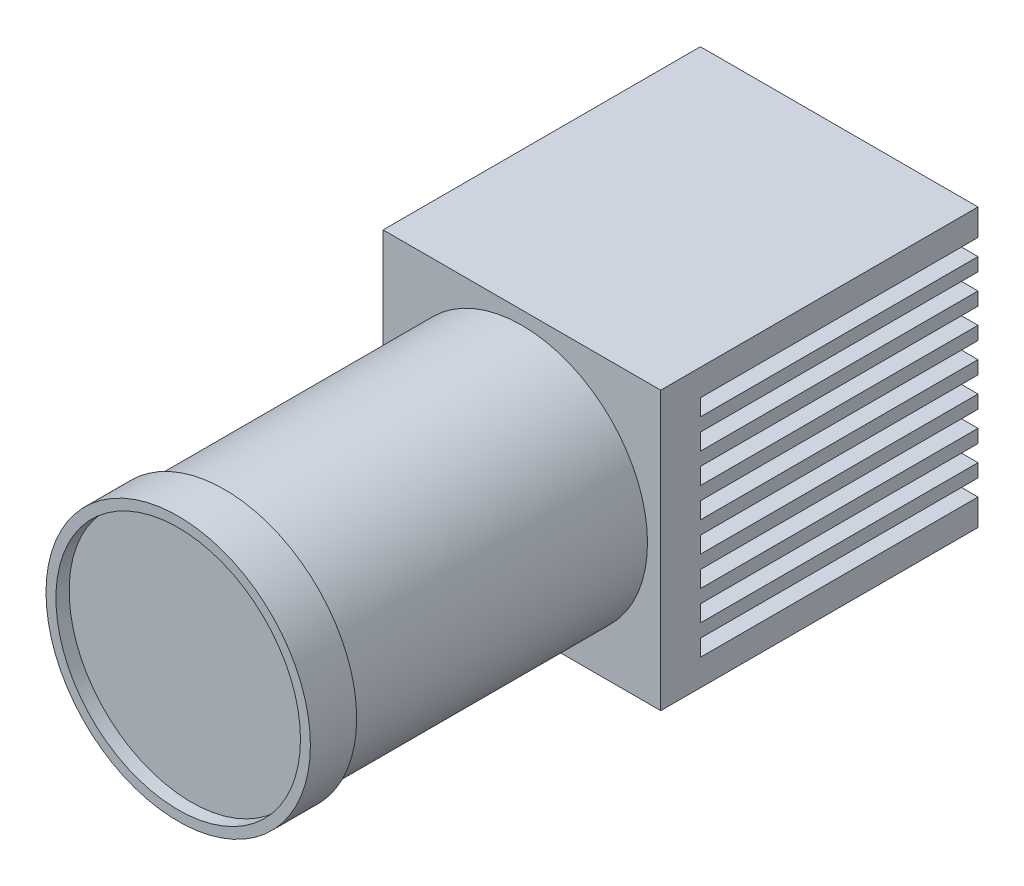
SolidWorks part; units mm, degrees
ref_plane "Front Plane" through (0, 0, 0) normal (0, 0, 1) x (1, 0, 0)
ref_plane "Top Plane" through (0, 0, 0) normal (0, 1, 0) x (1, 0, 0)
ref_plane "Right Plane" through (0, 0, 0) normal (1, 0, 0) x (0, 0, -1)
sketch "Sketch2" plane through (0, 0, 0) normal (0, 0, 1) x (1, 0, 0)
  line L1 (0, 0) -> (42, 0)
  line L2 (0, 0) -> (0, 42)
  line L3 (0, 42) -> (42, 42)
  line L4 (42, 0) -> (42, 42)
  dimension "D1" = 42
  dimension "D2" = 42
extrude "Boss-Extrude1" add sketch "Sketch2" along normal blind 48
sketch "Sketch3" plane through (0, 0, 48) normal (0, 0, 1) x (1, 0, 0)
  line L0 (0, 21) -> (42, 21) construction
  line L1 (0, 42) -> (0, 0) construction
  line L2 (42, 0) -> (42, 42) construction
  circle A0 centre (21, 21) radius 19
  dimension "D1" = 38
extrude "Boss-Extrude2" add sketch "Sketch3" along normal blind 50
sketch "Sketch4" plane through (0, 0, 98) normal (0, 0, 1) x (1, 0, 0)
  circle A0 centre (21, 21) radius 18.5
  circle A1 centre (21, 21) radius 20
  dimension "D1" = 37
  dimension "D2" = 40
extrude "Boss-Extrude3" add sketch "Sketch4" against normal blind 5 separate body
sketch "Sketch5" plane through (0, 0, 98) normal (0, 0, 1) x (1, 0, 0)
  circle A0 centre (21, 21) radius 18.5
  circle A1 centre (21, 21) radius 20
extrude "Boss-Extrude4" add sketch "Sketch5" along normal blind 2
ref_plane "Plane1" through (21, 0, 0) normal (1, 0, 0) x (0, 0, -1)
sketch "Sketch6" plane through (0, 0, 0) normal (0, 0, -1) x (-1, 0, 0)
  line L0 (-42, 0) -> (-42, 42) construction
  line L1 (-42, 38) -> (-39.5, 38)
  line L2 (-42, 38) -> (-42, 35.5)
  line L3 (-42, 35.5) -> (-39.5, 35.5)
  line L4 (-39.5, 38) -> (-39.5, 35.5)
  line L5 (-42, 6.5) -> (-39.5, 6.5)
  line L6 (-42, 33.5) -> (-39.5, 33.5)
  line L7 (-42, 33.5) -> (-42, 31)
  line L8 (-42, 31) -> (-39.5, 31)
  line L9 (-39.5, 33.5) -> (-39.5, 31)
  line L10 (-42, 24.5) -> (-39.5, 24.5)
  line L11 (-42, 24.5) -> (-42, 22)
  line L12 (-42, 22) -> (-39.5, 22)
  line L13 (-39.5, 24.5) -> (-39.5, 22)
  line L14 (-42, 20) -> (-39.5, 20)
  line L15 (-42, 20) -> (-42, 17.5)
  line L16 (-42, 17.5) -> (-39.5, 17.5)
  line L17 (-39.5, 20) -> (-39.5, 17.5)
  line L18 (-42, 15.5) -> (-39.5, 15.5)
  line L19 (-42, 15.5) -> (-42, 13)
  line L20 (-42, 13) -> (-39.5, 13)
  line L21 (-39.5, 15.5) -> (-39.5, 13)
  line L22 (-42, 11) -> (-39.5, 11)
  line L23 (-42, 11) -> (-42, 8.5)
  line L24 (-42, 8.5) -> (-39.5, 8.5)
  line L25 (-39.5, 11) -> (-39.5, 8.5)
  line L26 (-42, 29) -> (-39.5, 29)
  line L27 (-42, 29) -> (-42, 26.5)
  line L28 (-42, 26.5) -> (-39.5, 26.5)
  line L29 (-39.5, 29) -> (-39.5, 26.5)
  line L30 (-42, 6.5) -> (-42, 4)
  line L31 (-42, 4) -> (-39.5, 4)
  line L32 (-39.5, 6.5) -> (-39.5, 4)
  line L33 (-42, 42) -> (0, 42) construction
  line L34 (-21, 23.1) -> (-21, -23.1) construction
  line L35 (-2.5, 6.5) -> (-2.5, 4)
  line L36 (0, 4) -> (-2.5, 4)
  line L37 (0, 6.5) -> (0, 4)
  line L38 (-2.5, 29) -> (-2.5, 26.5)
  line L39 (0, 26.5) -> (-2.5, 26.5)
  line L40 (0, 29) -> (0, 26.5)
  line L41 (0, 29) -> (-2.5, 29)
  line L42 (-2.5, 11) -> (-2.5, 8.5)
  line L43 (0, 8.5) -> (-2.5, 8.5)
  line L44 (0, 11) -> (0, 8.5)
  line L45 (0, 11) -> (-2.5, 11)
  line L46 (-2.5, 15.5) -> (-2.5, 13)
  line L47 (0, 13) -> (-2.5, 13)
  line L48 (0, 15.5) -> (0, 13)
  line L49 (0, 15.5) -> (-2.5, 15.5)
  line L50 (-2.5, 20) -> (-2.5, 17.5)
  line L51 (0, 17.5) -> (-2.5, 17.5)
  line L52 (0, 20) -> (0, 17.5)
  line L53 (0, 20) -> (-2.5, 20)
  line L54 (-2.5, 24.5) -> (-2.5, 22)
  line L55 (0, 22) -> (-2.5, 22)
  line L56 (0, 24.5) -> (0, 22)
  line L57 (0, 24.5) -> (-2.5, 24.5)
  line L58 (-2.5, 33.5) -> (-2.5, 31)
  line L59 (0, 31) -> (-2.5, 31)
  line L60 (0, 33.5) -> (0, 31)
  line L61 (0, 33.5) -> (-2.5, 33.5)
  line L62 (0, 6.5) -> (-2.5, 6.5)
  line L63 (-2.5, 38) -> (-2.5, 35.5)
  line L64 (0, 35.5) -> (-2.5, 35.5)
  line L65 (0, 38) -> (0, 35.5)
  line L66 (0, 38) -> (-2.5, 38)
  dimension "D1" = 2.5
  dimension "D2" = 2.5
  dimension "D3" = 2.5
  dimension "D4" = 2.5
  dimension "D5" = 2.5
  dimension "D6" = 2.5
  dimension "D7" = 2.5
  dimension "D8" = 2.5
  dimension "D9" = 2.5
  dimension "D10" = 2.5
  dimension "D11" = 2.5
  dimension "D12" = 2.5
  dimension "D13" = 2.5
  dimension "D14" = 2.5
  dimension "D15" = 2
  dimension "D16" = 2
  dimension "D17" = 2
  dimension "D18" = 2
  dimension "D19" = 2
  dimension "D20" = 2
  dimension "D21" = 2.5
  dimension "D22" = 2.5
  dimension "D23" = 2
  dimension "D24" = 4
extrude "Cut-Extrude1" cut sketch "Sketch6" against normal blind 42
